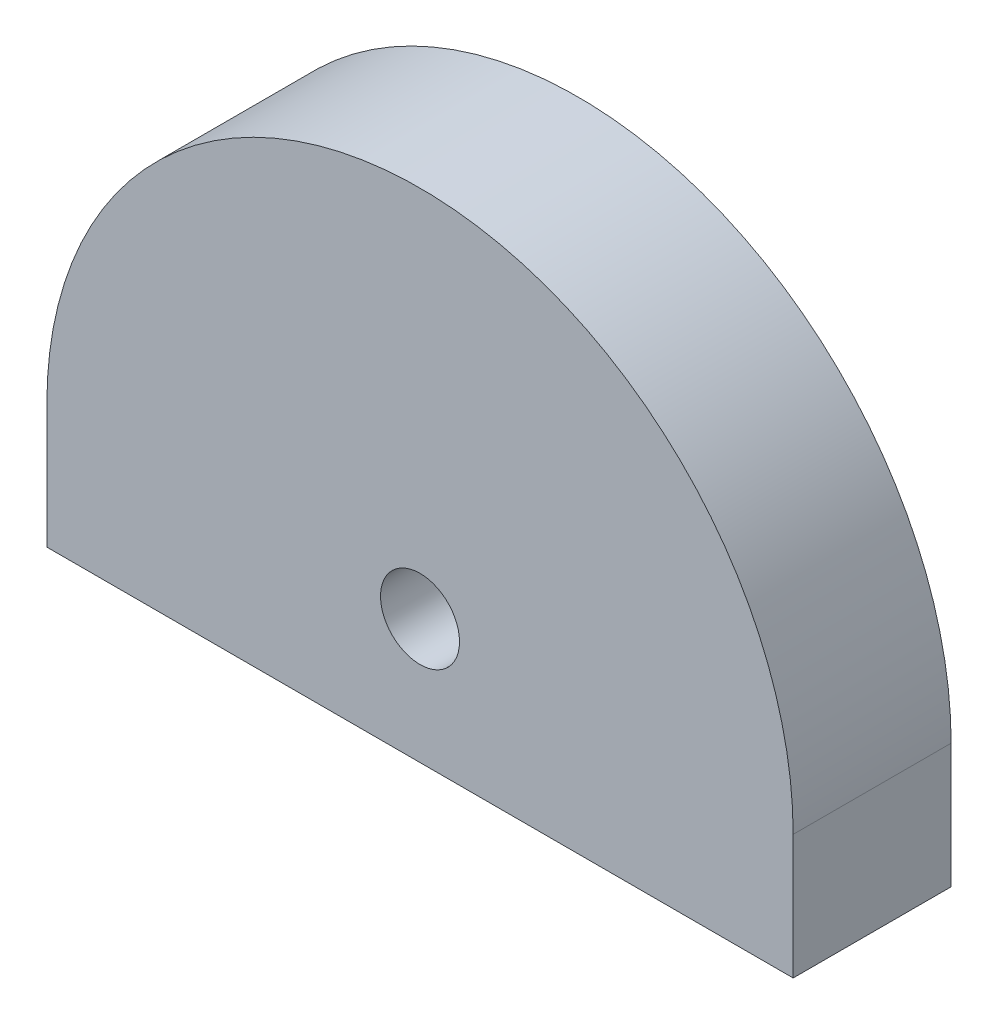
SolidWorks part; units mm, degrees
ref_plane "Alzado" through (0, 0, 0) normal (0, 0, 1) x (1, 0, 0)
ref_plane "Planta" through (0, 0, 0) normal (0, 1, 0) x (1, 0, 0)
ref_plane "Vista lateral" through (0, 0, 0) normal (1, 0, 0) x (0, 0, -1)
sketch "Croquis1" plane through (0, 0, 0) normal (0, 0, 1) x (1, 0, 0)
  line L0 (0, 10) -> (0, 0) construction
  line L1 (30, 10) -> (30, 0)
  line L2 (-30, 10) -> (-30, 0)
  line L3 (-30, 0) -> (30, 0)
  arc A0 (30, 10) -> (-30, 10) centre (0, 10) ccw
  circle A1 centre (0, 10) radius 3.175
  point P10 (0, 0)
  dimension "D1" = 30
  dimension "D3" = 6.35
  dimension "D2" = 10
extrude "Saliente-Extruir1" add sketch "Croquis1" along normal mid plane 12.7
